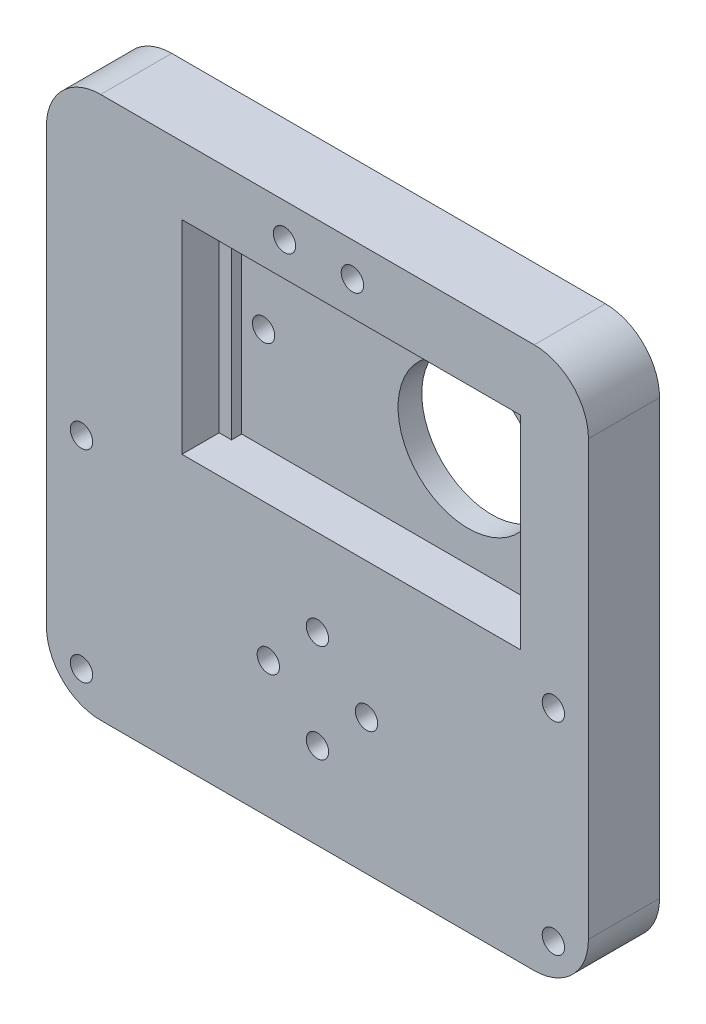
SolidWorks part; units mm, degrees
ref_plane "前视基准面" through (0, 0, 0) normal (0, 0, 1) x (1, 0, 0)
ref_plane "上视基准面" through (0, 0, 0) normal (0, 1, 0) x (1, 0, 0)
ref_plane "右视基准面" through (0, 0, 0) normal (1, 0, 0) x (0, 0, -1)
sketch "草图1" plane through (0, 0, 0) normal (0, 0, 1) x (1, 0, 0)
  line L1 (-45, 40) -> (35, 40)
  line L2 (-45, 40) -> (-45, -40)
  line L3 (-45, -40) -> (35, -40)
  line L4 (35, 40) -> (35, -40)
extrude "凸台-拉伸1" add sketch "草图1" along normal blind 10.5
sketch "草图2" plane through (0, 0, 10.5) normal (0, 0, 1) x (1, 0, 0)
  line L1 (-25, 30) -> (25, 30)
  line L2 (-25, 30) -> (-25, 0)
  line L3 (-25, 0) -> (25, 0)
  line L4 (25, 30) -> (25, 0)
sketch "草图3" plane through (0, 0, 10.5) normal (0, 0, 1) x (1, 0, 0)
  line L0 (10.25, 15) -> (-19.95, 15) construction
  line L1 (-16.0291, 15) -> (-16.0291, 35) construction
  line L2 (-16.0291, 35) -> (26.8141, 35) construction
  circle A0 centre (10.25, 15) radius 10.35
  circle A4 centre (-19.95, 15) radius 1.65
  circle A5 centre (10.25, 15) radius 22.4 construction
  circle A6 centre (-19.95, 15) radius 22.4 construction
  circle A7 centre (-9.8624, 35) radius 1.65
  circle A8 centre (0.1624, 35) radius 1.65
  point P0 (10.25, 15)
  point P8 (0.1624, 35)
  point P11 (-9.8624, 35)
extrude "切除-拉伸1" cut sketch "草图3" against normal through all
sketch "草图5" plane through (-45, 0, 0) normal (-1, 0, 0) x (0, 0, 1)
  line L0 (0, -11.3386) -> (10.5, -11.3386)
  line L1 (0, -44) -> (0, 44) construction
  line L2 (10.5, 40) -> (10.5, -40) construction
  dimension "D1" = 10.5
sketch "草图6" plane through (0, 0, 10.5) normal (0, 0, 1) x (1, 0, 0)
  line L0 (-25, 30) -> (25, 30) construction
  line L1 (-23.1809, 30) -> (22.0742, 30)
  line L2 (-23.1809, 30) -> (-23.1809, 0)
  line L3 (-23.1809, 0) -> (22.0742, 0)
  line L4 (22.0742, 30) -> (22.0742, 0)
  line L5 (-25, 0) -> (25, 0) construction
extrude "切除-拉伸2" cut sketch "草图2" against normal blind 5.5
extrude "切除-拉伸3" cut sketch "草图6" against normal blind 7
sketch "草图7" plane through (0, 0, 10.5) normal (0, 0, 1) x (1, 0, 0)
  circle A0 centre (-5, -20) radius 7.25
  circle A1 centre (-5, -12.75) radius 1.65
  circle A2 centre (2.25, -20) radius 1.65
  circle A3 centre (-5, -27.25) radius 1.65
  circle A4 centre (-12.25, -20) radius 1.65
  point P0 (-5, -20)
extrude "切除-拉伸4" cut sketch "草图7" against normal through all contours A2 | A3 | A4 | A1
fillet "圆角1" radius 8 1 edges at (-45, -40, 5.25)
fillet "圆角2" radius 8 1 edges at (35, -40, 5.25)
fillet "圆角3" radius 8 1 edges at (35, 40, 5.25)
fillet "圆角4" radius 8 1 edges at (-45, 40, 5.25)
sketch "草图8" plane through (0, 0, 10.5) normal (0, 0, 1) x (1, 0, 0)
  line L0 (-45, -6.185) -> (35, -6.185)
  line L1 (-45, 32) -> (-45, -32) construction
  line L2 (35, -32) -> (35, 32) construction
  line L3 (27, 40) -> (-37, 40) construction
  line L4 (-29.6831, 40) -> (-29.6831, -40)
  line L5 (-37, -40) -> (27, -40) construction
sketch "草图9" plane through (0, 0, 0) normal (0, 0, -1) x (-1, 0, 0)
  line L0 (-27, -32) -> (-32.6569, -37.6569) construction
  line L1 (37, -32) -> (42.6569, -37.6569) construction
  line L2 (39.8284, 0) -> (39.8284, -5) construction
  line L3 (-29.8284, 0) -> (-29.8284, -5) construction
  arc A0 (-35, -32) -> (-27, -40) centre (-27, -32) ccw construction
  circle A1 centre (-29.8284, -34.8284) radius 1.65
  arc A2 (37, -40) -> (45, -32) centre (37, -32) ccw construction
  circle A3 centre (39.8284, -34.8284) radius 1.65
  circle A4 centre (-29.8284, -5) radius 1.65
  circle A5 centre (39.8284, -5) radius 1.65
  point P16 (39.8284, 0)
  point P17 (-29.8284, 0)
extrude "切除-拉伸5" cut sketch "草图9" against normal through all
